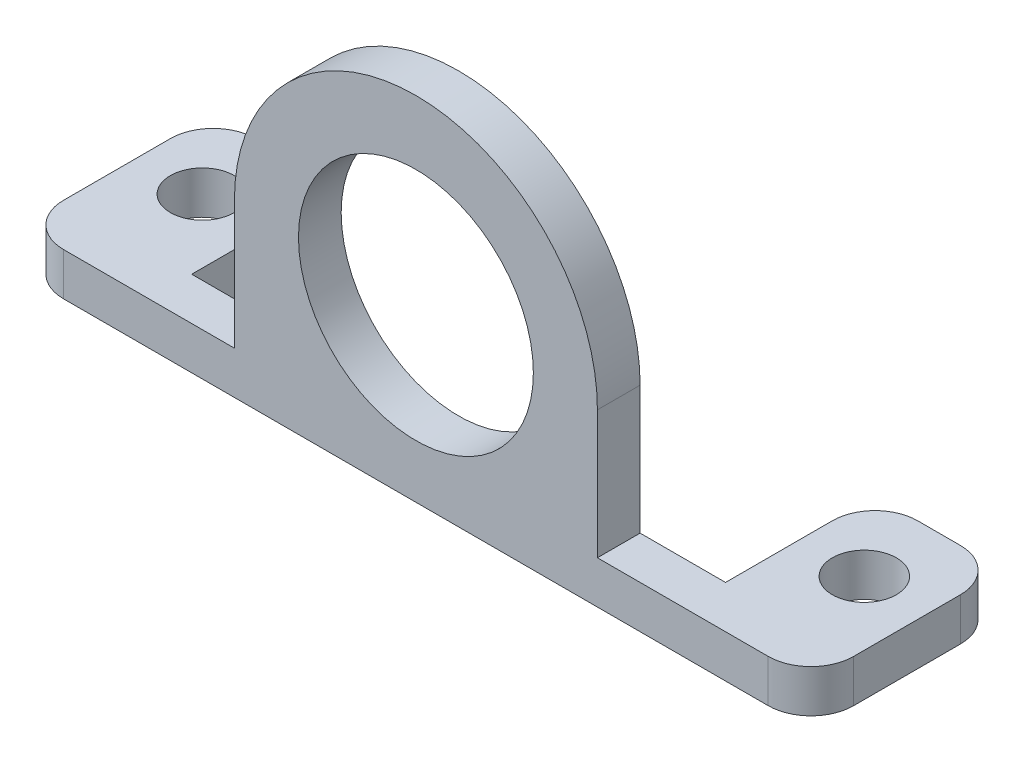
SolidWorks part; units mm, degrees
ref_plane "前视基准面" through (0, 0, 0) normal (0, 0, 1) x (1, 0, 0)
ref_plane "上视基准面" through (0, 0, 0) normal (0, 1, 0) x (1, 0, 0)
ref_plane "右视基准面" through (0, 0, 0) normal (1, 0, 0) x (0, 0, -1)
sketch "草图1" plane through (0, 0, 0) normal (0, 1, 0) x (1, 0, 0)
  line L0 (0, 0) -> (-15.5, 0) construction
  line L1 (0, 0) -> (0, 8.3622) construction
  line L2 (-12.5, -3.5) -> (12.5, -3.5)
  line L3 (-18.5, -3.5) -> (-12.5, -3.5) construction
  line L4 (-18.5, -3.5) -> (-18.5, 3.5)
  line L5 (-18.5, 3.5) -> (-12.5, 3.5)
  line L6 (-12.5, -3.5) -> (-12.5, 3.5)
  line L7 (-18.5, -3.5) -> (-12.5, 3.5) construction
  line L8 (-18.5, 3.5) -> (-12.5, -3.5) construction
  line L9 (-18.5, -3.5) -> (-18.5, -5.5)
  line L10 (-18.5, -5.5) -> (18.5, -5.5)
  line L11 (18.5, -3.5) -> (18.5, -5.5)
  line L12 (18.5, -3.5) -> (18.5, 3.5)
  line L13 (12.5, -3.5) -> (12.5, 3.5)
  line L14 (18.5, 3.5) -> (12.5, 3.5)
  circle A0 centre (-15.5, 0) radius 1.5
  circle A1 centre (15.5, 0) radius 1.5
  point P16 (0, -5.5)
  point P17 (0, -3.5)
  dimension "D1" = 3
  dimension "D2" = 31
  dimension "D3" = 6
  dimension "D4" = 7
  dimension "D5" = 2
extrude "凸台-拉伸1" add sketch "草图1" along normal blind 2
sketch "草图2" plane through (0, 0, 5.5) normal (0, 0, 1) x (1, 0, 0)
  line L0 (0, 0) -> (0, 8) construction
  line L1 (-18.5, 0) -> (18.5, 0) construction
  line L2 (-8.5, 8) -> (-8.5, 0)
  line L3 (-8.5, 0) -> (8.5, 0)
  line L4 (8.5, 0) -> (8.5, 8)
  circle A0 centre (0, 8) radius 5.5
  arc A1 (8.5, 8) -> (-8.5, 8) centre (0, 8) ccw
  dimension "D2" = 3
  dimension "D3" = 11
  dimension "D1" = 8
extrude "凸台-拉伸2" add sketch "草图2" against normal blind 2
fillet "圆角1" radius 2 6 edges at (-18.5, 1, 5.5) (18.5, 1, 5.5) (12.5, 1, -3.5) (18.5, 1, -3.5) (-12.5, 1, -3.5) (-18.5, 1, -3.5)
